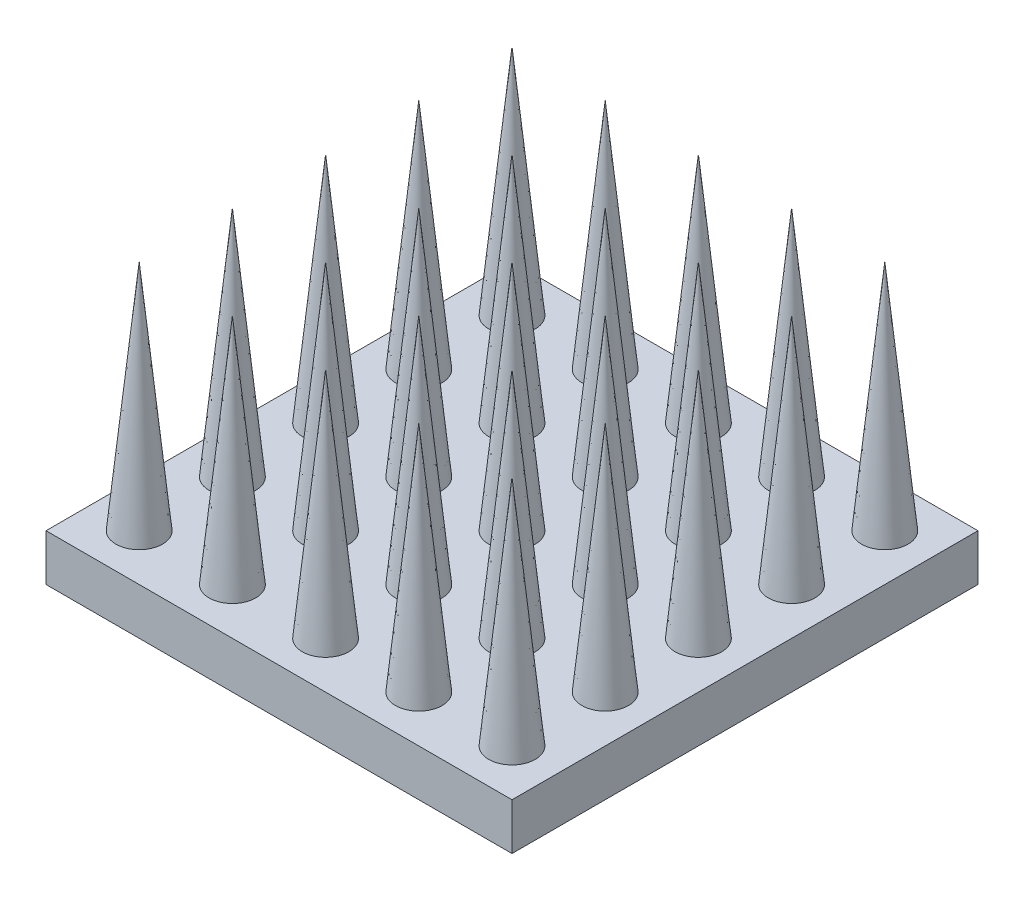
SolidWorks part; units mm, degrees
ref_plane "前基準面" through (0, 0, 0) normal (0, 0, 1) x (1, 0, 0)
ref_plane "上基準面" through (0, 0, 0) normal (0, 1, 0) x (1, 0, 0)
ref_plane "右基準面" through (0, 0, 0) normal (1, 0, 0) x (0, 0, -1)
sketch "草圖1" plane through (0, 0, 0) normal (0, 1, 0) x (1, 0, 0)
  line L1 (-5, 5) -> (5, 5)
  line L2 (-5, 5) -> (-5, -5)
  line L3 (-5, -5) -> (5, -5)
  line L4 (5, 5) -> (5, -5)
  line L5 (-5, 5) -> (5, -5) construction
  line L6 (-5, -5) -> (5, 5) construction
  point P0 (0, 0)
  dimension "D1" = 10
  dimension "D2" = 10
extrude "填料-伸長1" add sketch "草圖1" along normal blind 1 contours L1 L4 L3 L2
ref_plane "平面1" through (0, 0, -4) normal (0, 0, -1) x (-1, 0, 0)
sketch "草圖4" plane through (0, 0, -4) normal (0, 0, -1) x (-1, 0, 0)
  line L0 (-4, 1) -> (-4, 6)
  line L1 (5, 1) -> (-5, 1) construction
  line L4 (-3.5, 1) -> (-4, 6)
  line L5 (-3.5, 1) -> (-4, 1)
revolve "旋轉1" add sketch "草圖4" angle 360 about L0
pattern_linear "直線複製排列8" count 5 spacing 2 along (0, 0, 1) of bodies 102
pattern_linear "直線複製排列9" count 5 spacing 2 along (-1, 0, 0) of bodies 106 105 104 103 102
